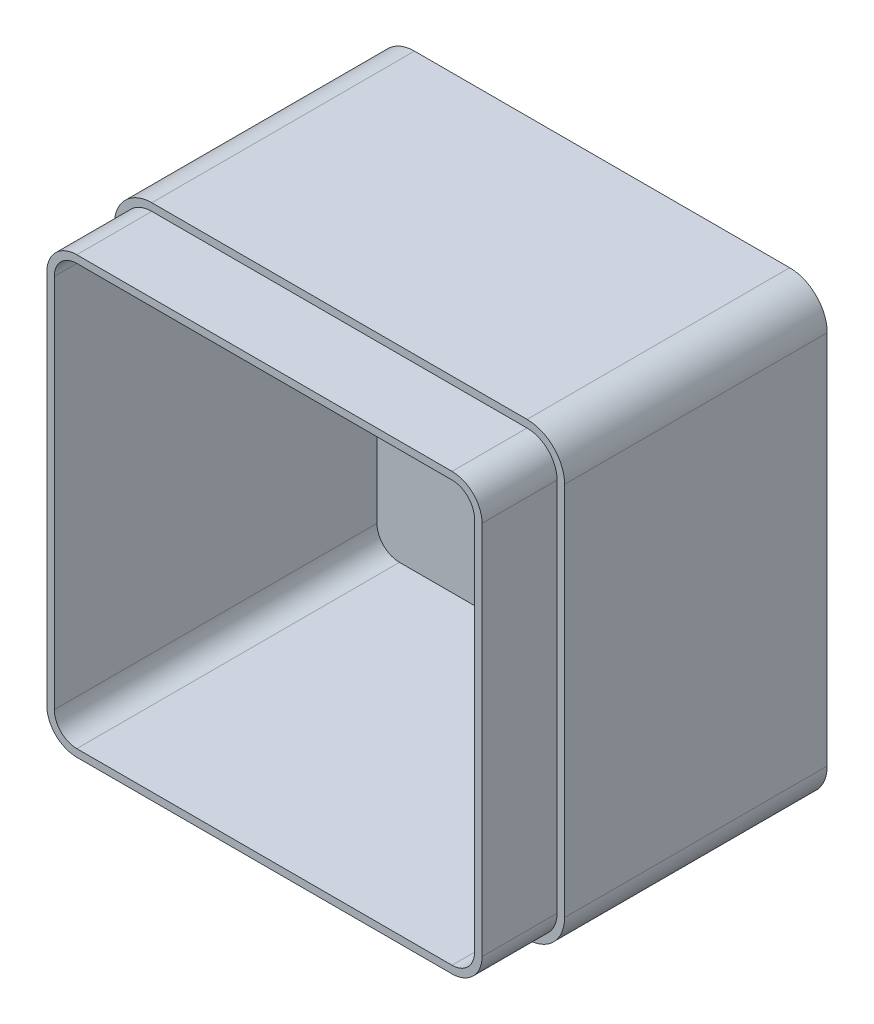
SolidWorks part; units mm, degrees
ref_plane "Front" through (0, 0, 0) normal (0, 0, 1) x (1, 0, 0)
ref_plane "Top" through (0, 0, 0) normal (0, 1, 0) x (1, 0, 0)
ref_plane "Right" through (0, 0, 0) normal (1, 0, 0) x (0, 0, -1)
sketch "Sketch1" plane through (0, 0, 0) normal (0, 0, 1) x (1, 0, 0)
  line L1 (0, 0) -> (120, 0)
  line L2 (0, 0) -> (0, 120)
  line L3 (0, 120) -> (120, 120)
  line L4 (120, 0) -> (120, 120)
  line L5 (0, 0) -> (120, 120) construction
  line L6 (0, 120) -> (120, 0) construction
  point P4 (60, 60)
  dimension "D1" = 120
  dimension "D2" = 120
extrude "Boss-Extrude1" add sketch "Sketch1" along normal blind 90
fillet "Fillet1" radius 10 4 edges at (0, 0, 45) (120, 0, 45) (120, 120, 45) (0, 120, 45)
shell "Shell1" thickness 4
sketch "Sketch2" plane through (0, 0, 90) normal (0, 0, 1) x (1, 0, 0)
  line L4 (0, 110) -> (0, 10)
  line L5 (10, 0) -> (110, 0)
  line L6 (120, 10) -> (120, 110)
  line L7 (110, 120) -> (10, 120)
  line L8 (0, 110) -> (0, 10)
  line L9 (10, 0) -> (110, 0)
  line L10 (120, 10) -> (120, 110)
  line L11 (110, 120) -> (10, 120)
  line L16 (2, 110) -> (2, 10)
  line L17 (10, 2) -> (110, 2)
  line L18 (118, 10) -> (118, 110)
  line L19 (110, 118) -> (10, 118)
  line L20 (2, 110) -> (2, 10)
  line L21 (10, 2) -> (110, 2)
  line L22 (118, 10) -> (118, 110)
  line L23 (110, 118) -> (10, 118)
  arc A4 (0, 10) -> (10, 0) centre (10, 10) ccw
  arc A5 (110, 0) -> (120, 10) centre (110, 10) ccw
  arc A6 (120, 110) -> (110, 120) centre (110, 110) ccw
  arc A7 (10, 120) -> (0, 110) centre (10, 110) ccw
  arc A8 (0, 10) -> (10, 0) centre (10, 10) ccw
  arc A9 (110, 0) -> (120, 10) centre (110, 10) ccw
  arc A10 (120, 110) -> (110, 120) centre (110, 110) ccw
  arc A11 (10, 120) -> (0, 110) centre (10, 110) ccw
  arc A16 (2, 10) -> (10, 2) centre (10, 10) ccw
  arc A17 (110, 2) -> (118, 10) centre (110, 10) ccw
  arc A18 (118, 110) -> (110, 118) centre (110, 110) ccw
  arc A19 (10, 118) -> (2, 110) centre (10, 110) ccw
  arc A20 (2, 10) -> (10, 2) centre (10, 10) ccw
  arc A21 (110, 2) -> (118, 10) centre (110, 10) ccw
  arc A22 (118, 110) -> (110, 118) centre (110, 110) ccw
  arc A23 (10, 118) -> (2, 110) centre (10, 110) ccw
  dimension "D1" = 0
  dimension "D2" = 2
extrude "Cut-Extrude1" cut sketch "Sketch2" against normal blind 20
